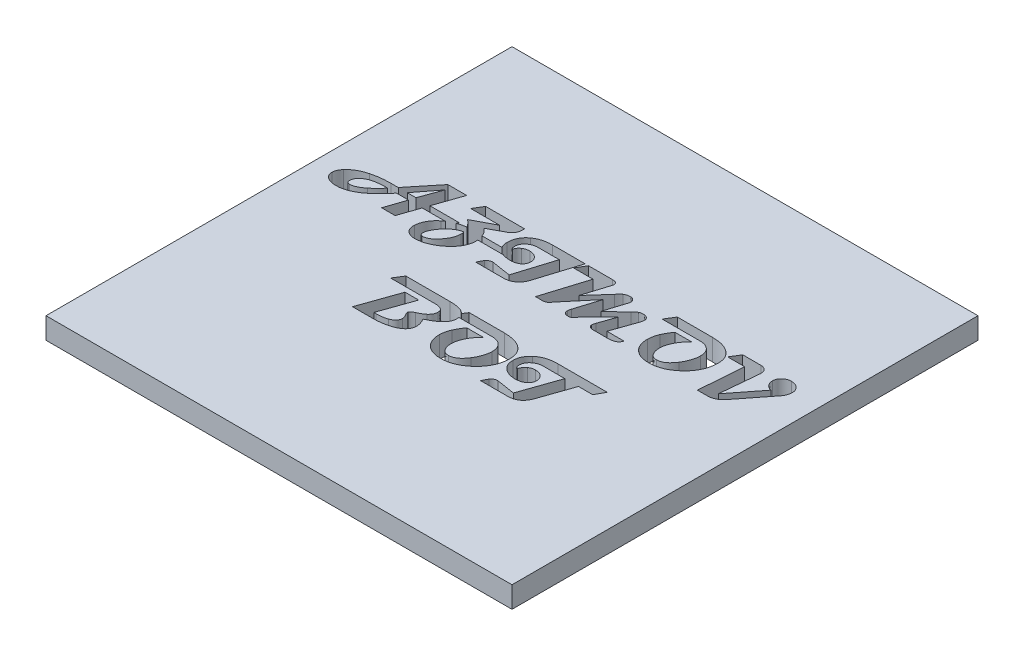
SolidWorks part; units mm, degrees
ref_plane "Спереди" through (0, 0, 0) normal (0, 0, 1) x (1, 0, 0)
ref_plane "Сверху" through (0, 0, 0) normal (0, 1, 0) x (1, 0, 0)
ref_plane "Справа" through (0, 0, 0) normal (1, 0, 0) x (0, 0, -1)
other "Configuration Table"
sketch "Эскиз1" plane through (0, 0, 0) normal (0, 1, 0) x (1, 0, 0)
  line L1 (35, -35) -> (-35, -35)
  line L2 (35, -35) -> (35, 35)
  line L3 (35, 35) -> (-35, 35)
  line L4 (-35, -35) -> (-35, 35)
  line L5 (35, -35) -> (-35, 35) construction
  line L6 (35, 35) -> (-35, -35) construction
  point P0 (0, 0)
  dimension "D1" = 70
  dimension "D2" = 70
extrude "Бобышка-Вытянуть1" add sketch "Эскиз1" along normal blind 3.2
sketch "Эскиз2" plane through (0, 3.2, 0) normal (0, 1, 0) x (1, 0, 0)
  text T0 "AZIMOV\r\n    BOT" font "Magneto" height 8
extrude "Вырез-Вытянуть1" cut sketch "Эскиз2" against normal blind 3.2
